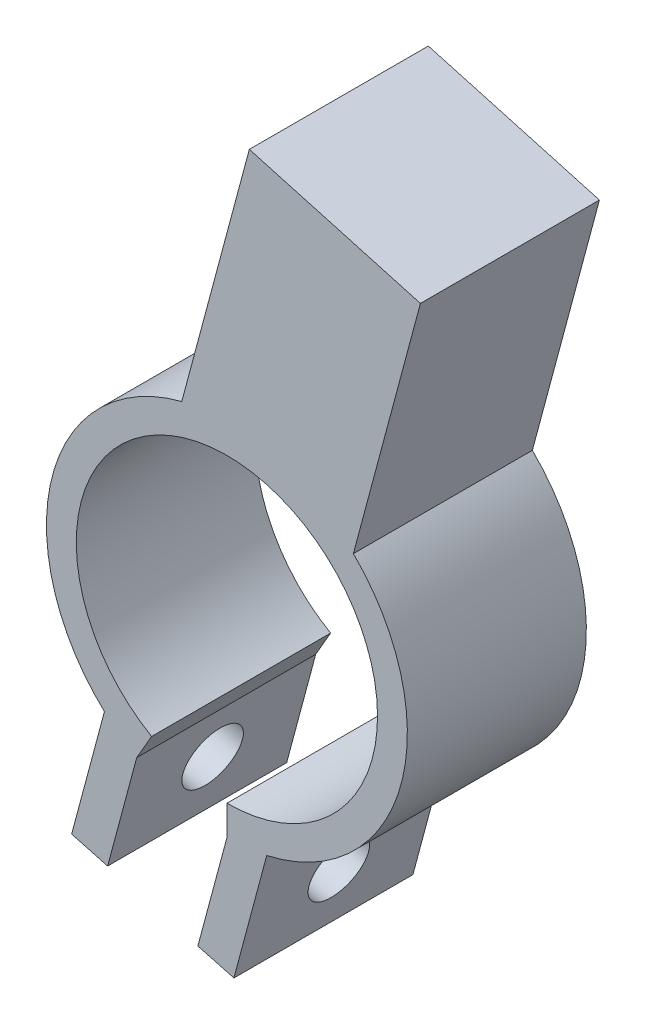
SolidWorks part; units mm, degrees
ref_plane "Front Plane" through (0, 0, 0) normal (0, 0, 1) x (1, 0, 0)
ref_plane "Top Plane" through (0, 0, 0) normal (0, 1, 0) x (1, 0, 0)
ref_plane "Right Plane" through (0, 0, 0) normal (1, 0, 0) x (0, 0, -1)
sketch "Sketch1" plane through (0, 0, 0) normal (0, 0, 1) x (1, 0, 0)
  circle A0 centre (0, 0) radius 20.193
  circle A1 centre (0, 0) radius 20.193 construction
  circle A2 centre (0, 0) radius 24.193
  dimension "D1" = 4
extrude "Boss-Extrude1" add sketch "Sketch1" along normal blind 24
sketch "Sketch2" plane through (0, 0, 24) normal (0, 0, 1) x (1, 0, 0)
  line L0 (0, -24.193) -> (-5.8342, -24.8953)
  line L1 (-5.8342, -24.8953) -> (-12.0965, -20.9518)
  line L2 (0, -24.193) -> (0, 0)
  line L3 (-12.0965, -20.9518) -> (0, 0)
  circle A0 centre (0, 0) radius 24.193 construction
  dimension "D1" = 7.4005
  dimension "D2" = 5.8342
  dimension "D3" = 30
extrude "Cut-Extrude1" cut sketch "Sketch2" against normal blind 24
sketch "Sketch3" plane through (0, 0, 24) normal (0, 0, 1) x (1, 0, 0)
  line L0 (-12.0965, -20.9518) -> (-15.99, -35.4826)
  line L1 (-15.99, -35.4826) -> (-20.8197, -34.1885)
  line L2 (-20.8197, -34.1885) -> (-16.4197, -17.7678)
  line L3 (-12.0965, -20.9518) -> (-16.4197, -17.7678)
  line L4 (0, -24.193) -> (5.336, -23.5972)
  line L5 (5.336, -23.5972) -> (0.9361, -40.0179)
  line L6 (0.9361, -40.0179) -> (-3.8935, -38.7238)
  line L7 (-3.8935, -38.7238) -> (0, -24.193)
  line L8 (-3.8935, -38.7238) -> (-15.99, -35.4826)
  line L9 (0, -24.193) -> (-12.0965, -20.9518)
  arc A0 (0, -24.193) -> (-12.0965, -20.9518) centre (0, 0) ccw construction
  arc M6 (0, -24.193) -> (-12.0965, -20.9518) centre (0, 0) ccw
  dimension "D1" = 17
  dimension "D2" = 5
extrude "Boss-Extrude2" add sketch "Sketch3" against normal blind 24 contours L2 L1 L0 M6 | L7 L6 L5 M6
sketch "Sketch4" plane through (-10.8779, 2.9147, 0) normal (-0.9659, 0.2588, 0) x (0, 0, 1)
  line L0 (12, -38.4121) -> (12, -30.4121)
  line L1 (0, -38.4121) -> (24, -38.4121) construction
  circle A0 centre (12, -30.4121) radius 4
  dimension "D2" = 8
  dimension "D1" = 8
extrude "Cut-Extrude2" cut sketch "Sketch4" against normal blind 24
sketch "Sketch5" plane through (0, 0, 24) normal (0, 0, 1) x (1, 0, 0)
  line L0 (0, -20.193) -> (-10.0965, -17.4877)
  line L3 (16.9534, 17.2593) -> (25.9449, 50.816)
  line L4 (25.9449, 50.816) -> (3.0062, 57.2311)
  line L5 (3.0062, 57.2311) -> (-6.0524, 23.4237)
  line L6 (16.9534, 17.2593) -> (-6.0524, 23.4237)
  arc A0 (5.336, -23.5972) -> (-16.4197, -17.7678) centre (0, 0) ccw construction
  arc M14 (5.336, -23.5972) -> (-16.4197, -17.7678) centre (0, 0) ccw
  dimension "D1" = 35
extrude "Boss-Extrude4" add sketch "Sketch5" against normal blind 24 contours L4 L5 L3 M14
